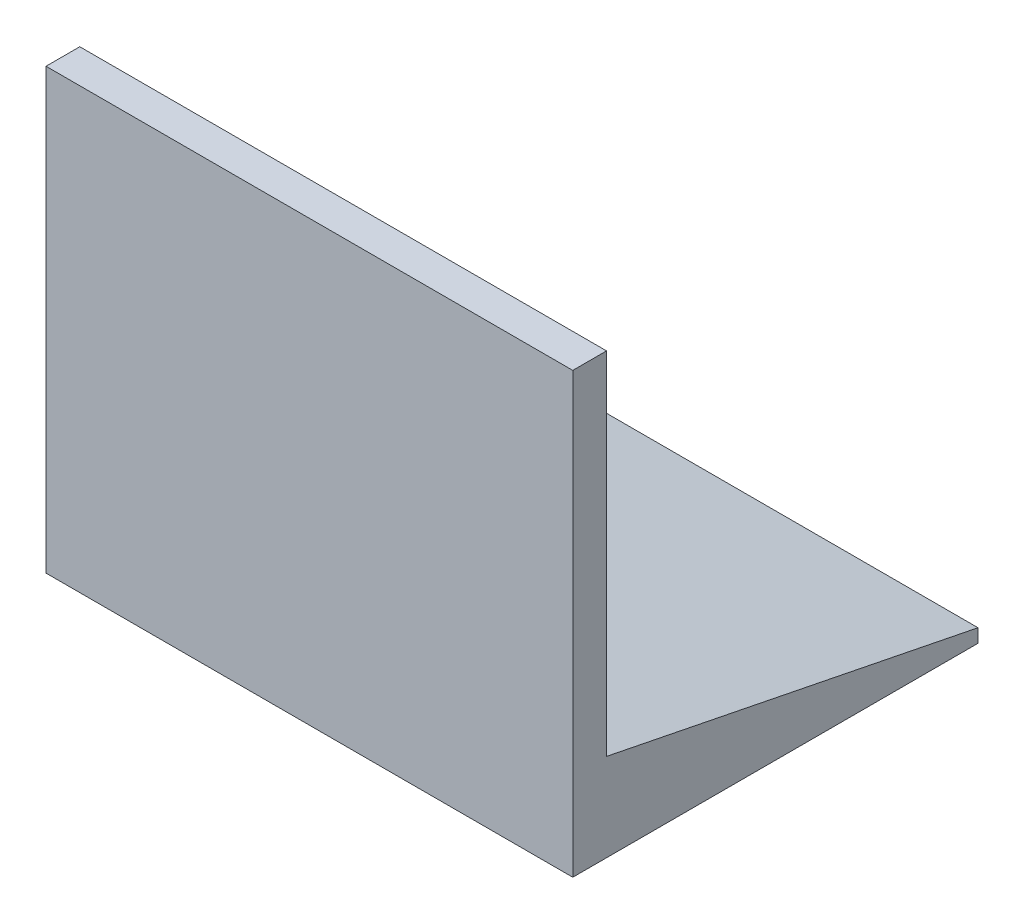
SolidWorks part; units mm, degrees
ref_plane "Front Plane" through (0, 0, 0) normal (0, 0, 1) x (1, 0, 0)
ref_plane "Top Plane" through (0, 0, 0) normal (0, 1, 0) x (1, 0, 0)
ref_plane "Right Plane" through (0, 0, 0) normal (1, 0, 0) x (0, 0, -1)
sketch "Sketch1" plane through (0, 0, 0) normal (1, 0, 0) x (0, 0, -1)
  line L0 (0, 0) -> (300, 0)
  line L1 (300, 0) -> (300, 10)
  line L2 (300, 10) -> (25, 65)
  line L3 (25, 65) -> (25, 325)
  line L4 (25, 325) -> (0, 325)
  line L5 (0, 325) -> (0, 0)
  line L6 (0, 0) -> (-1.4541, 3.6353)
  dimension "D1" = 325
  dimension "D2" = 300
  dimension "D3" = 260
  dimension "D4" = 25
  dimension "D5" = 10
extrude "Boss-Extrude1" add sketch "Sketch1" along normal blind 390 contours L4 L5 L0 L1 L2 L3
